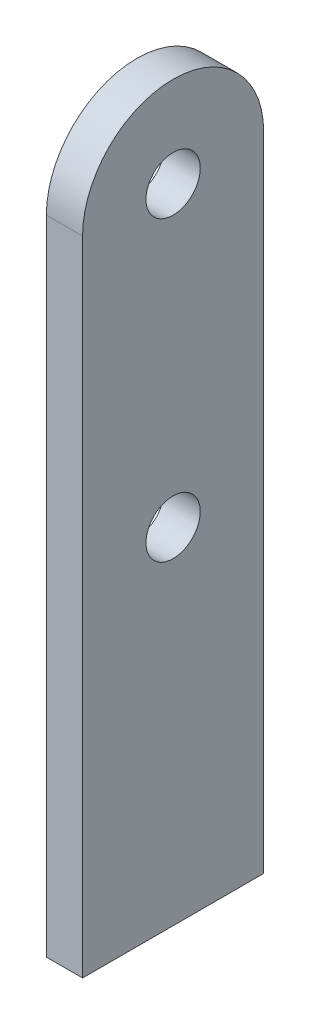
SolidWorks part; units mm, degrees
ref_plane "Front Plane" through (0, 0, 0) normal (0, 0, 1) x (1, 0, 0)
ref_plane "Top Plane" through (0, 0, 0) normal (0, 1, 0) x (1, 0, 0)
ref_plane "Right Plane" through (0, 0, 0) normal (1, 0, 0) x (0, 0, -1)
sketch "Sketch1" plane through (0, 0, 0) normal (1, 0, 0) x (0, 0, -1)
  line L0 (-25, 0) -> (25, 0)
  line L1 (-25, 177.4317) -> (-25, 0)
  line L2 (25, 177.4317) -> (25, 0)
  circle A0 centre (0, 95.2901) radius 7.5
  circle A1 centre (0, 177.4317) radius 7.5
  arc A2 (25, 177.4317) -> (-25, 177.4317) centre (0, 177.4317) ccw
  dimension "D1" = 15
  dimension "D2" = 15
  dimension "D5" = 50
  dimension "D3" = 95.2901
  dimension "D4" = 177.4317
extrude "Boss-Extrude1" add sketch "Sketch1" along normal blind 10
